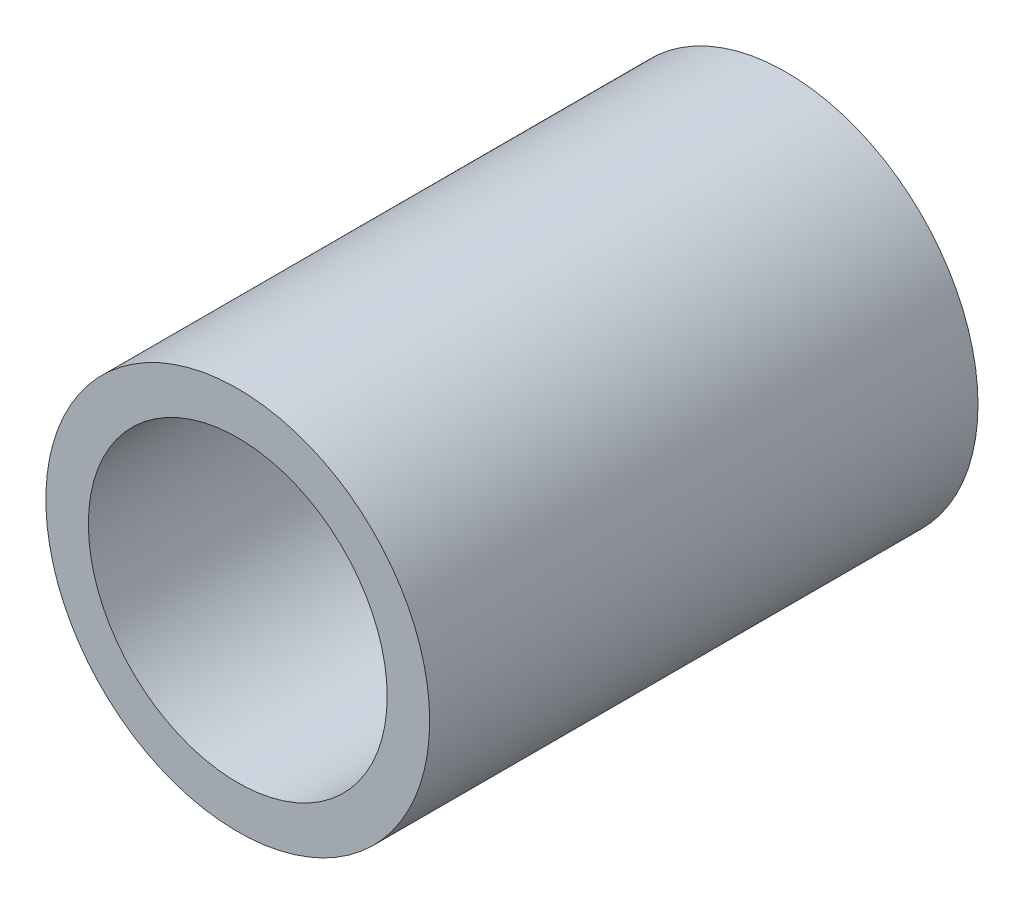
SolidWorks part; units mm, degrees
material "ABS"
ref_plane "Front Plane" through (0, 0, 0) normal (0, 0, 1) x (1, 0, 0)
ref_plane "Top Plane" through (0, 0, 0) normal (0, 1, 0) x (1, 0, 0)
ref_plane "Right Plane" through (0, 0, 0) normal (1, 0, 0) x (0, 0, -1)
sketch "Sketch1" plane through (0, 0, 0) normal (0, 0, 1) x (1, 0, 0)
  circle A0 centre (0, 0) radius 3.5
  circle A1 centre (0, 0) radius 2.725
  dimension "D1" = 5.45
  dimension "D2" = 7
extrude "Boss-Extrude1" add sketch "Sketch1" along normal blind 10
equation "\"D1@Sketch1\"=5+\"print_free@Parameters@Parameters.SLDPRT\""
